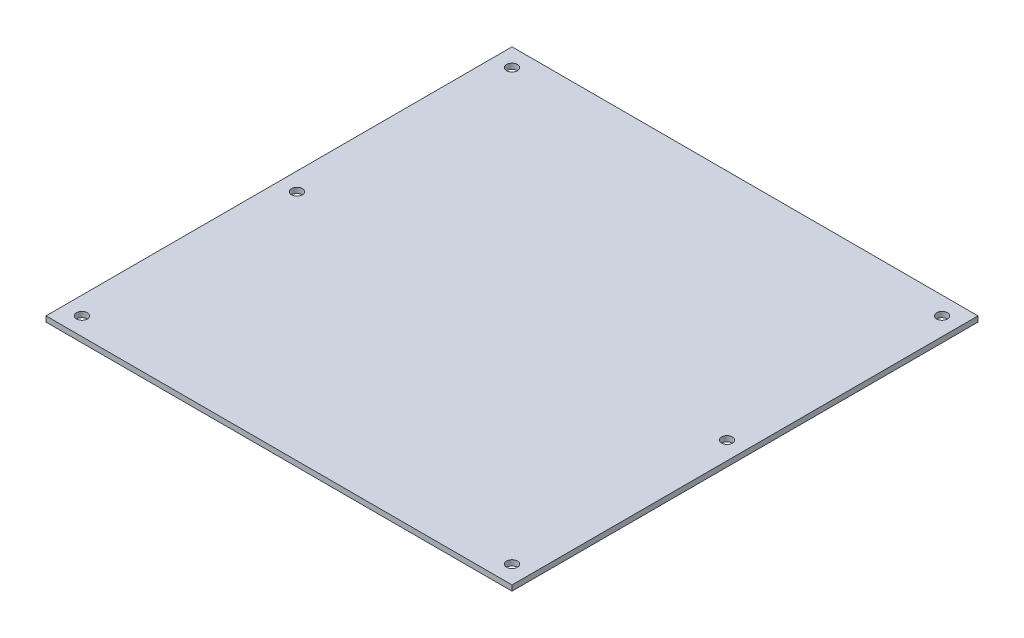
SolidWorks part; units mm, degrees
material "Pine"
ref_plane "Front Plane" through (0, 0, 0) normal (0, 0, 1) x (1, 0, 0)
ref_plane "Top Plane" through (0, 0, 0) normal (0, 1, 0) x (1, 0, 0)
ref_plane "Right Plane" through (0, 0, 0) normal (1, 0, 0) x (0, 0, -1)
sketch "Sketch1" plane through (0, 0, 0) normal (0, 1, 0) x (1, 0, 0)
  line L1 (171.45, -171.45) -> (-171.45, -171.45)
  line L2 (171.45, -171.45) -> (171.45, 171.45)
  line L3 (171.45, 171.45) -> (-171.45, 171.45)
  line L4 (-171.45, -171.45) -> (-171.45, 171.45)
  line L5 (171.45, -171.45) -> (-171.45, 171.45) construction
  line L6 (171.45, 171.45) -> (-171.45, -171.45) construction
  point P0 (0, 0)
  dimension "D1" = 342.9
extrude "Boss-Extrude1" add sketch "Sketch1" along normal blind 4
sketch "Sketch2" plane through (0, 4, 0) normal (0, 1, 0) x (1, 0, 0)
  line L0 (-158.225, 158.225) -> (158.225, -158.225) construction
  line L1 (158.225, 158.225) -> (-158.225, -158.225) construction
  line L2 (-145, 0) -> (-171.45, 0) construction
  line L3 (145, -145) -> (-145, -145) construction
  line L4 (145, -145) -> (145, 145) construction
  line L5 (145, 145) -> (-145, 145) construction
  line L6 (-145, -145) -> (-145, 145) construction
  line L7 (145, -145) -> (-145, 145) construction
  line L8 (145, 145) -> (-145, -145) construction
  line L9 (-171.45, 171.45) -> (-171.45, -171.45) construction
  circle A0 centre (-158.225, 158.225) radius 4
  circle A1 centre (-158.225, 0) radius 4
  circle A2 centre (-158.225, -158.225) radius 4
  circle A3 centre (158.225, 158.225) radius 4
  circle A4 centre (158.225, 0) radius 4
  circle A5 centre (158.225, -158.225) radius 4
  point P13 (0, 0)
  dimension "D1" = 8
  dimension "D2" = 290
extrude "Cut-Extrude1" cut sketch "Sketch2" against normal through all
